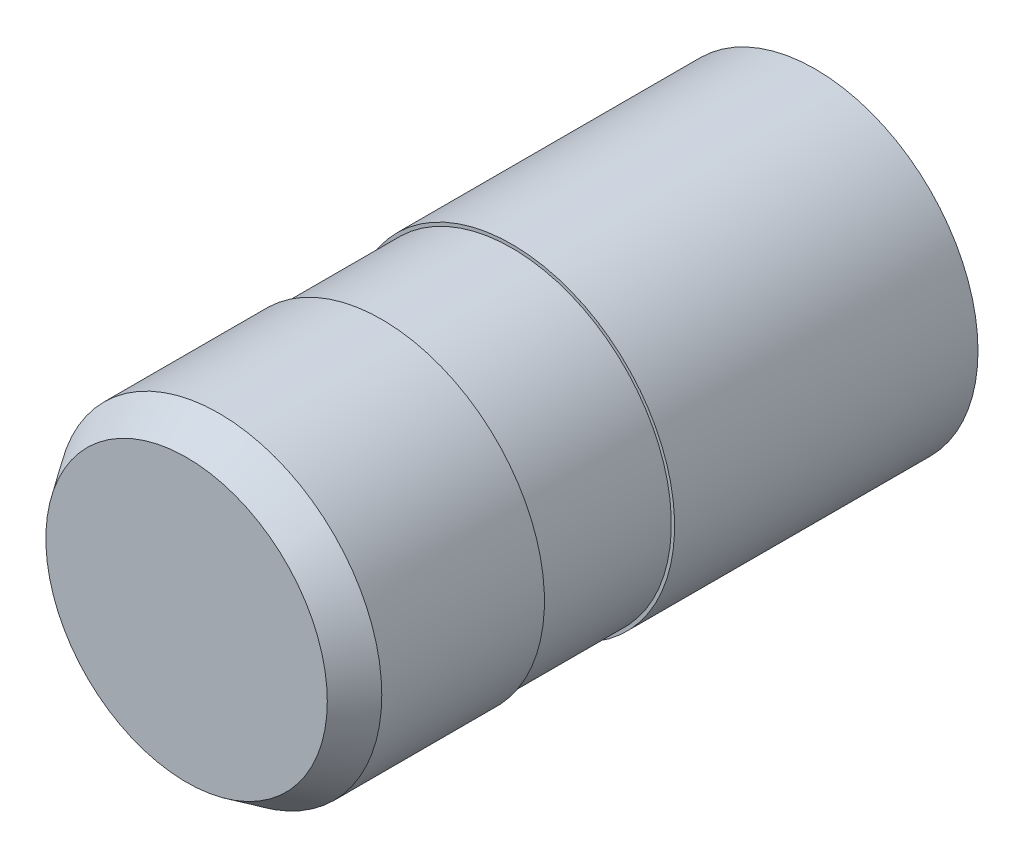
SolidWorks part; units mm, degrees
ref_plane "前视基准面" through (0, 0, 0) normal (0, 0, 1) x (1, 0, 0)
ref_plane "上视基准面" through (0, 0, 0) normal (0, 1, 0) x (1, 0, 0)
ref_plane "右视基准面" through (0, 0, 0) normal (1, 0, 0) x (0, 0, -1)
sketch "草图1" plane through (0, 0, 0) normal (0, 0, 1) x (1, 0, 0)
  circle A0 centre (0, 0) radius 25
  dimension "D1" = 50
extrude "凸台-拉伸1" add sketch "草图1" along normal mid plane 100
chamfer "倒角1" distance 5 angle 34 2 edges at (25, 0, 50) (25, 0, -50)
ref_plane "基准面1" through (0, 0, 0) normal (0, 0, -1) x (-1, 0, 0)
sketch "草图2" plane through (0, 0, 0) normal (0, 0, -1) x (-1, 0, 0)
  circle A0 centre (0, 0) radius 25 construction
  circle A1 centre (0, 0) radius 25
  circle A2 centre (0, 0) radius 24.5
  dimension "D1" = 0.5
extrude "切除-拉伸1" cut sketch "草图2" against normal blind 20
